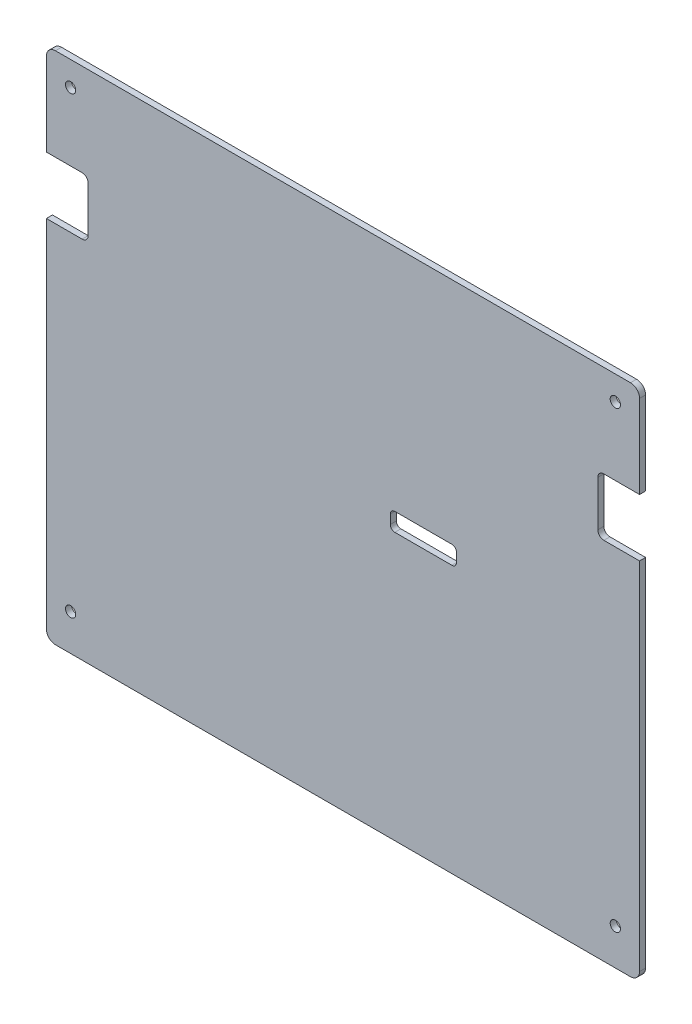
SolidWorks part; units mm, degrees
ref_plane "Спереди" through (0, 0, 0) normal (0, 0, 1) x (1, 0, 0)
ref_plane "Сверху" through (0, 0, 0) normal (0, 1, 0) x (1, 0, 0)
ref_plane "Справа" through (0, 0, 0) normal (1, 0, 0) x (0, 0, -1)
other "Configuration Table"
sketch "Acrylic_2mm_profile" plane through (0, 0, 0) normal (0, 0, 1) x (1, 0, 0)
  line L0 (0, -7) -> (190, -7)
  line L1 (193, -4) -> (193, 160)
  line L2 (190, 163) -> (0, 163)
  line L3 (-3, 160) -> (-3, -4)
  arc A0 (190, -7) -> (193, -4) centre (190, -4) ccw
  arc A1 (193, 160) -> (190, 163) centre (190, 160) ccw
  arc A2 (0, 163) -> (-3, 160) centre (0, 160) ccw
  arc A3 (-3, -4) -> (0, -7) centre (0, -4) ccw
extrude "Acrylic_2mm" add sketch "Acrylic_2mm_profile" along normal blind 2 from offset 12
sketch "Hinge_clearance_0_profile" plane through (0, 0, 0) normal (0, 0, 1) x (1, 0, 0)
  line L0 (-4, 113.5) -> (8.8, 113.5)
  line L1 (10.8, 115.5) -> (10.8, 130.5)
  line L2 (8.8, 132.5) -> (-4, 132.5)
  line L3 (-6, 130.5) -> (-6, 115.5)
  arc A0 (8.8, 113.5) -> (10.8, 115.5) centre (8.8, 115.5) ccw
  arc A1 (10.8, 130.5) -> (8.8, 132.5) centre (8.8, 130.5) ccw
  arc A2 (-4, 132.5) -> (-6, 130.5) centre (-4, 130.5) ccw
  arc A3 (-6, 115.5) -> (-4, 113.5) centre (-4, 115.5) ccw
extrude "Hinge_clearance_0" cut sketch "Hinge_clearance_0_profile" against normal blind 2.4 from offset 9.8
sketch "Hinge_clearance_1_profile" plane through (0, 0, 0) normal (0, 0, 1) x (1, 0, 0)
  line L0 (181.2, 113.5) -> (194, 113.5)
  line L1 (196, 115.5) -> (196, 130.5)
  line L2 (194, 132.5) -> (181.2, 132.5)
  line L3 (179.2, 130.5) -> (179.2, 115.5)
  arc A0 (194, 113.5) -> (196, 115.5) centre (194, 115.5) ccw
  arc A1 (196, 130.5) -> (194, 132.5) centre (194, 130.5) ccw
  arc A2 (181.2, 132.5) -> (179.2, 130.5) centre (181.2, 130.5) ccw
  arc A3 (179.2, 115.5) -> (181.2, 113.5) centre (181.2, 115.5) ccw
extrude "Hinge_clearance_1" cut sketch "Hinge_clearance_1_profile" against normal blind 2.4 from offset 9.8
sketch "M3_clearance_0_profile" plane through (0, 0, 0) normal (0, 0, 1) x (1, 0, 0)
  circle A0 centre (5, 5) radius 1.7
extrude "M3_clearance_0" cut sketch "M3_clearance_0_profile" against normal blind 2.4 from offset 9.8
sketch "M3_clearance_1_profile" plane through (0, 0, 0) normal (0, 0, 1) x (1, 0, 0)
  circle A0 centre (185, 5) radius 1.7
extrude "M3_clearance_1" cut sketch "M3_clearance_1_profile" against normal blind 2.4 from offset 9.8
sketch "M3_clearance_2_profile" plane through (0, 0, 0) normal (0, 0, 1) x (1, 0, 0)
  circle A0 centre (5, 155) radius 1.7
extrude "M3_clearance_2" cut sketch "M3_clearance_2_profile" against normal blind 2.4 from offset 9.8
sketch "M3_clearance_3_profile" plane through (0, 0, 0) normal (0, 0, 1) x (1, 0, 0)
  circle A0 centre (185, 155) radius 1.7
extrude "M3_clearance_3" cut sketch "M3_clearance_3_profile" against normal blind 2.4 from offset 9.8
sketch "Keys_access_R1_5_profile" plane through (0, 0, 0) normal (0, 0, 1) x (1, 0, 0)
  line L0 (112.125, 81.25) -> (131, 81.25)
  line L1 (132.5, 82.75) -> (132.5, 85.75)
  line L2 (131, 87.25) -> (112.125, 87.25)
  line L3 (110.625, 85.75) -> (110.625, 82.75)
  arc A0 (131, 81.25) -> (132.5, 82.75) centre (131, 82.75) ccw
  arc A1 (132.5, 85.75) -> (131, 87.25) centre (131, 85.75) ccw
  arc A2 (112.125, 87.25) -> (110.625, 85.75) centre (112.125, 85.75) ccw
  arc A3 (110.625, 82.75) -> (112.125, 81.25) centre (112.125, 82.75) ccw
extrude "Keys_access_R1_5" cut sketch "Keys_access_R1_5_profile" against normal blind 2.4 from offset 9.8
